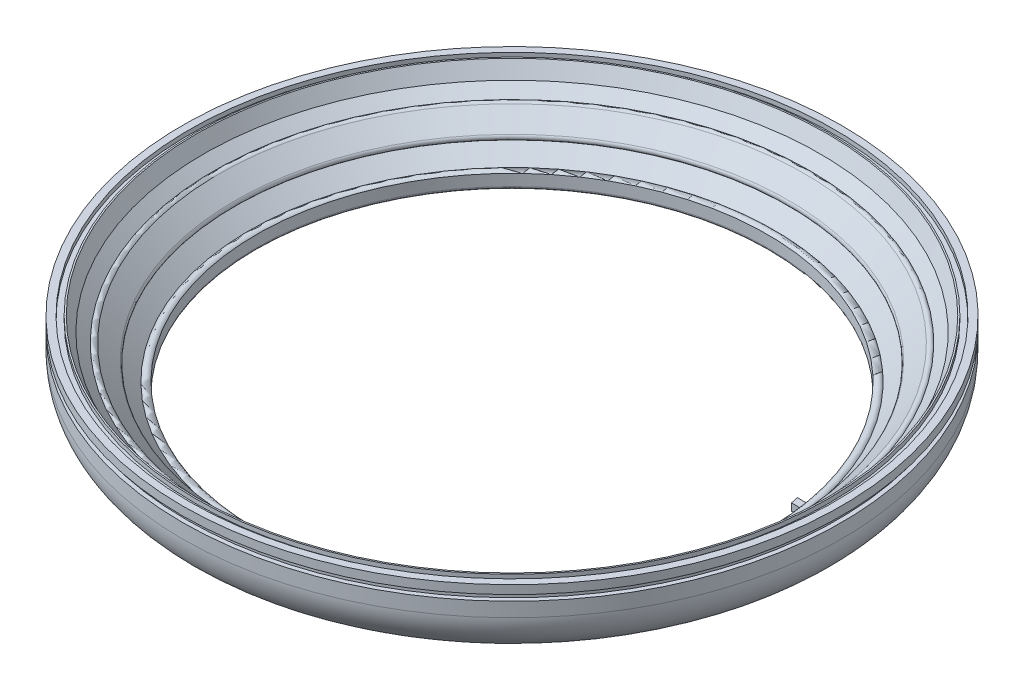
SolidWorks part; units mm, degrees
ref_plane "Front Plane" through (0, 0, 0) normal (0, 0, 1) x (1, 0, 0)
ref_plane "Top Plane" through (0, 0, 0) normal (0, 1, 0) x (1, 0, 0)
ref_plane "Right Plane" through (0, 0, 0) normal (1, 0, 0) x (0, 0, -1)
sketch "Sketch1" plane through (0, 0, 0) normal (0, 0, 1) x (1, 0, 0)
  line L0 (0, -0.0033) -> (-23.0091, -0.0033) construction
  line L1 (0, 2.809) -> (0, -0.0033) construction
  line L2 (-23.0091, -0.0033) -> (-23.0091, 3.9967)
  line L3 (-23.0091, 3.9967) -> (-22.7091, 3.9967)
  line L4 (-22.7091, 3.9967) -> (-22.7091, 4.3967)
  line L5 (-22.7091, 4.3967) -> (-23.0091, 4.3967)
  line L6 (-22.5112, 4.9967) -> (-23.0091, 4.9967)
  line L7 (-23.0091, 4.9967) -> (-23.0091, 4.3967)
  line L8 (-22.5112, 4.9967) -> (-22.5112, 4.6967)
  line L9 (-22.5112, 4.6967) -> (-22.1122, 4.6967)
  line L10 (-22.1122, 4.6967) -> (-22.1122, 4.9967)
  line L11 (-22.1122, 4.9967) -> (-22.0077, 4.9967)
  line L12 (-22.0077, 4.9967) -> (-21.5338, 4.004)
  line L13 (-23.0091, -0.0033) -> (-17.8266, -0.0033)
  line L14 (-17.8266, -0.0033) -> (-17.8266, 0.9967)
  line L19 (-18.3221, 0.9966) -> (-19.3361, 1.9461)
  line L23 (-20.8223, 3.3378) -> (-21.5338, 4.004)
  line L24 (-20.4576, 3.3378) -> (-19.3361, 2.2876)
  arc A0 (-18.3221, 0.9966) -> (-17.8266, 0.9967) centre (-18.0743, 0.7645) cw
  arc A7 (-20.4576, 3.3378) -> (-20.8223, 3.3378) centre (-20.64, 3.1554) ccw
  arc A8 (-19.3361, 2.2876) -> (-19.3361, 1.9461) centre (-19.5069, 2.1168) cw
revolve "Revolve1" add sketch "Sketch1" angle 360 about L1
fillet "Fillet1" radius 3 1 edges at (0, -0.0033, 23.0091)
fillet "Fillet2" radius 0.2 1 edges at (0, -0.0033, 17.8266)
sketch "Sketch2" plane through (0, 0, 0) normal (0, 1, 0) x (1, 0, 0)
  line L0 (23, 0) -> (0, 0) construction
  line L1 (0, 0) -> (-23, 0) construction
  line L2 (0, 0) -> (0, 23) construction
  line L3 (0, 0) -> (0, -23) construction
  line L4 (23, 0) -> (23, 2)
  line L5 (23, 0) -> (23, -2)
  line L6 (-23, 0) -> (-23, 2)
  line L7 (-23, 0) -> (-23, -2)
  line L8 (0, 23) -> (-2, 23)
  line L9 (0, 23) -> (2, 23)
  line L10 (0, -23) -> (-2, -23)
  line L11 (0, -23) -> (2, -23)
  line L13 (19.516, 3.4527) -> (15.9673, 3.4527)
  line L14 (19.516, 3.4527) -> (19.516, 2.9327)
  line L15 (19.516, 2.9327) -> (15.9673, 2.9327)
  line L16 (15.9673, 3.4527) -> (15.9673, 2.9327)
  line L17 (19.516, 3.4527) -> (15.9673, 2.9327) construction
  line L18 (19.516, 2.9327) -> (15.9673, 3.4527) construction
  circle A0 centre (0, 0) radius 18.0266 construction
  point P2 (17.7416, 3.1927)
sketch "Sketch3" plane through (0, 0, 0) normal (1, 0, 0) x (0, 0, -1)
  line L0 (-21.8, 0) -> (-21.8, 4)
  line L1 (0, 0) -> (-23, 0) construction
  line L2 (21.8, 0) -> (21.8, 0.8193)
  line L3 (0, 0) -> (23, 0) construction
sketch "Sketch4" plane through (0, 0, 0) normal (1, 0, 0) x (0, 0, -1)
  line L0 (-23.0091, 0) -> (-23.0091, 2.5)
  line L2 (0, 0) -> (-23, 0) construction
  line L3 (-23.0091, 2.5) -> (-23.0091, 4.9967)
  line L4 (-23.0091, 2.5) -> (-23.0091, 3.7484)
  line L5 (0, 0) -> (23, 0) construction
  line L7 (23.0091, 0) -> (23.0091, 4.9967)
  line L8 (23.0091, 2.4984) -> (23.0091, 3.8827)
sketch "Sketch5" plane through (0, 0, 0) normal (0, 0, 1) x (1, 0, 0)
  line L0 (23.0091, 0) -> (23.0091, 2.9967)
  line L2 (23, 0) -> (0, 0) construction
  line L3 (23.0091, 2.9967) -> (23.0091, 3.9967) construction
  line L4 (-23.0091, 2.9967) -> (23.0091, 2.9967) construction
  line L5 (23.0091, 2.9967) -> (23.0091, 4.9967)
  line L6 (-23.0091, 0) -> (-23.0091, 2.9967)
  line L7 (0, 0) -> (-23, 0) construction
  line L8 (-23.0091, 2.9967) -> (-23.0091, 4.9967)
extrude "Boss-Extrude2" add sketch "Sketch2" along normal blind 0.5 contours L13 L16 L15 L14
sketch "Sketch6" plane through (0, 0, 0) normal (0, 1, 0) x (1, 0, 0)
  line L0 (16.6404, 2.6745) -> (16.3818, 3.8497)
extrude "Cut-Extrude3" cut sketch "Sketch6" against normal through all and the other way through all
